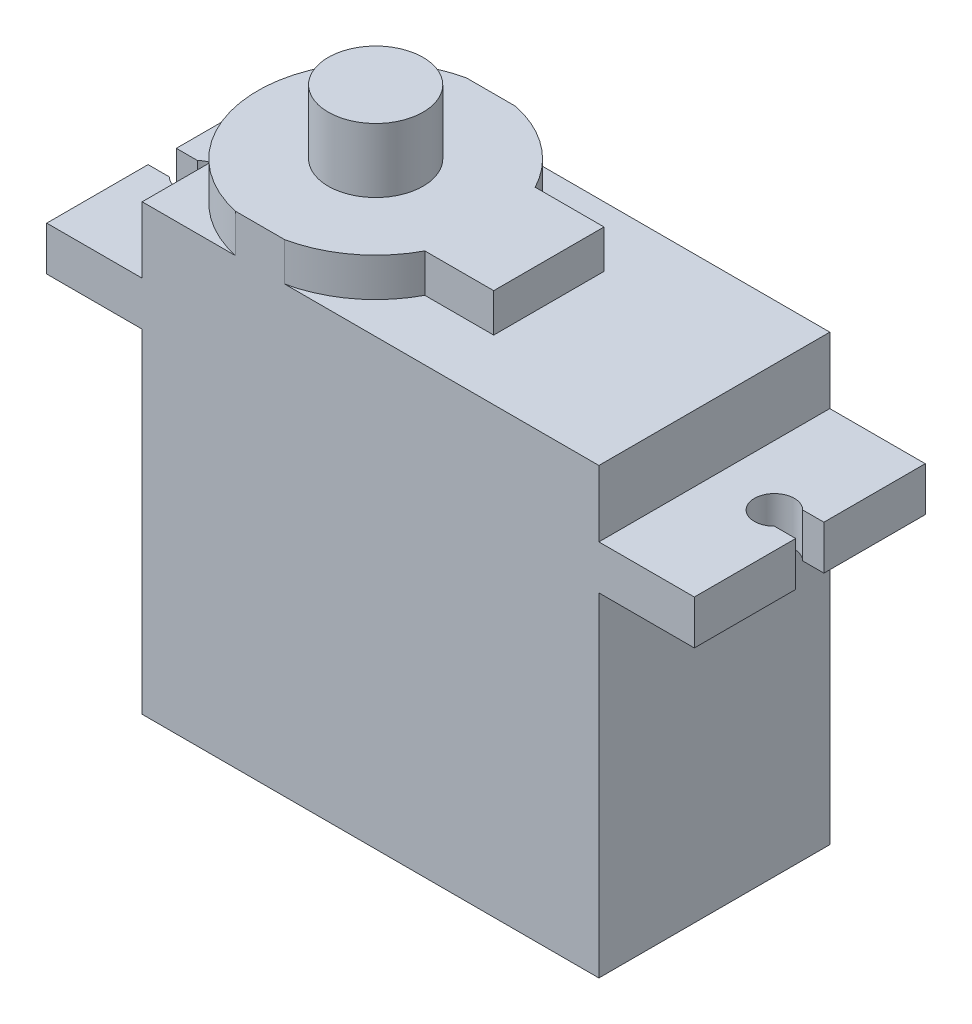
SolidWorks part; units mm, degrees
ref_plane "Front Plane" through (0, 0, 0) normal (0, 0, 1) x (1, 0, 0)
ref_plane "Top Plane" through (0, 0, 0) normal (0, 1, 0) x (1, 0, 0)
ref_plane "Right Plane" through (0, 0, 0) normal (1, 0, 0) x (0, 0, -1)
sketch "Sketch1" plane through (0, 0, 0) normal (0, 1, 0) x (1, 0, 0)
  line L1 (0, 0) -> (22.606, 0)
  line L2 (0, 0) -> (0, 11.43)
  line L3 (0, 11.43) -> (22.606, 11.43)
  line L4 (22.606, 0) -> (22.606, 11.43)
  dimension "D1" = 22.606
  dimension "D2" = 11.43
extrude "Boss-Extrude1" add sketch "Sketch1" along normal blind 21.971
ref_plane "Mounting Plane" through (0, 16.51, 0) normal (0, 1, 0) x (1, 0, 0)
sketch "Sketch3" plane through (0, 16.51, 0) normal (0, 1, 0) x (1, 0, 0)
  line L0 (22.606, 11.43) -> (0, 11.43) construction
  line L1 (0, 0) -> (-4.7244, 0)
  line L2 (0, 0) -> (0, 11.43)
  line L3 (0, 11.43) -> (-4.7244, 11.43)
  line L4 (-4.7244, 0) -> (-4.7244, 5.0165)
  line L5 (11.303, 11.43) -> (11.303, 0) construction
  line L6 (0, 0) -> (22.606, 0) construction
  line L7 (-4.1993, 5.715) -> (33.3353, 5.715) construction
  line L8 (-4.7244, 6.4135) -> (-4.7244, 11.43)
  line L9 (-3.6742, 5.0165) -> (-4.7244, 5.0165)
  line L10 (-3.6742, 5.0165) -> (-3.6742, 6.4135) construction
  line L11 (-3.6742, 6.4135) -> (-4.7244, 6.4135)
  line L13 (-3.6742, 5.0165) -> (-4.7244, 6.4135) construction
  line L14 (-3.6742, 6.4135) -> (-4.7244, 5.0165) construction
  arc A0 (-3.6742, 5.0165) -> (-3.6742, 6.4135) centre (-2.9718, 5.715) ccw
  point P14 (11.303, 5.715)
  point P15 (-4.1993, 5.715)
  dimension "D2" = 1.9812
  dimension "D1" = 4.7244
  dimension "D3" = 2.9718
  dimension "D4" = 1.397
extrude "Boss-Extrude2" add sketch "Sketch3" along normal blind 2.1844
ref_plane "Servo Mid-Plane" through (11.303, 0, 0) normal (1, 0, 0) x (0, 0, -1)
sketch "Sketch4" plane through (0, 21.971, 0) normal (0, 1, 0) x (1, 0, 0)
  line L0 (0, 5.715) -> (22.606, 5.715) construction
  line L1 (0, 0) -> (0, 11.43) construction
  line L2 (22.606, 0) -> (22.606, 11.43) construction
  line L3 (0, 11.43) -> (22.606, 11.43) construction
  line L4 (22.606, 0) -> (0, 0) construction
  line L5 (4.6305, 11.43) -> (7.0535, 11.43)
  line L6 (4.6305, 0) -> (7.0535, 0)
  line L8 (11.0066, 2.9845) -> (14.4145, 2.9845)
  line L10 (11.0066, 8.4455) -> (14.4145, 8.4455)
  line L11 (14.4145, 2.9845) -> (14.4145, 8.4455)
  line L12 (8.9535, 2.9845) -> (14.4145, 8.4455) construction
  line L13 (8.9535, 8.4455) -> (14.4145, 2.9845) construction
  arc A0 (4.6305, 11.43) -> (4.6305, 0) centre (5.842, 5.715) ccw
  arc A1 (7.0535, 0) -> (11.0066, 2.9845) centre (5.842, 5.715) ccw
  arc A2 (11.0066, 8.4455) -> (7.0535, 11.43) centre (5.842, 5.715) ccw
  point P7 (11.684, 5.715)
  dimension "D1" = 5.842
  dimension "D2" = 5.461
  dimension "D3" = 5.842
extrude "Boss-Extrude3" add sketch "Sketch4" along normal blind 1.905
sketch "Sketch5" plane through (0, 23.876, 0) normal (0, 1, 0) x (1, 0, 0)
  line L0 (0, 5.715) -> (11.303, 5.715) construction
  line L1 (11.303, -6.2866) -> (11.303, 6.2866) construction
  line L2 (5.842, 11.43) -> (5.842, 0) construction
  line L3 (7.0535, 11.43) -> (4.6305, 11.43) construction
  line L4 (4.6305, 0) -> (7.0535, 0) construction
  arc A0 (4.6305, 11.43) -> (4.6305, 0) centre (5.842, 5.715) ccw construction
  circle A2 centre (5.842, 5.715) radius 2.3495
  dimension "D1" = 4.699
extrude "Boss-Extrude4" add sketch "Sketch5" along normal blind 3.175
mirror "Mirror1" about plane through (11.303, 0, 0) normal (1, 0, 0) of "Boss-Extrude2"
